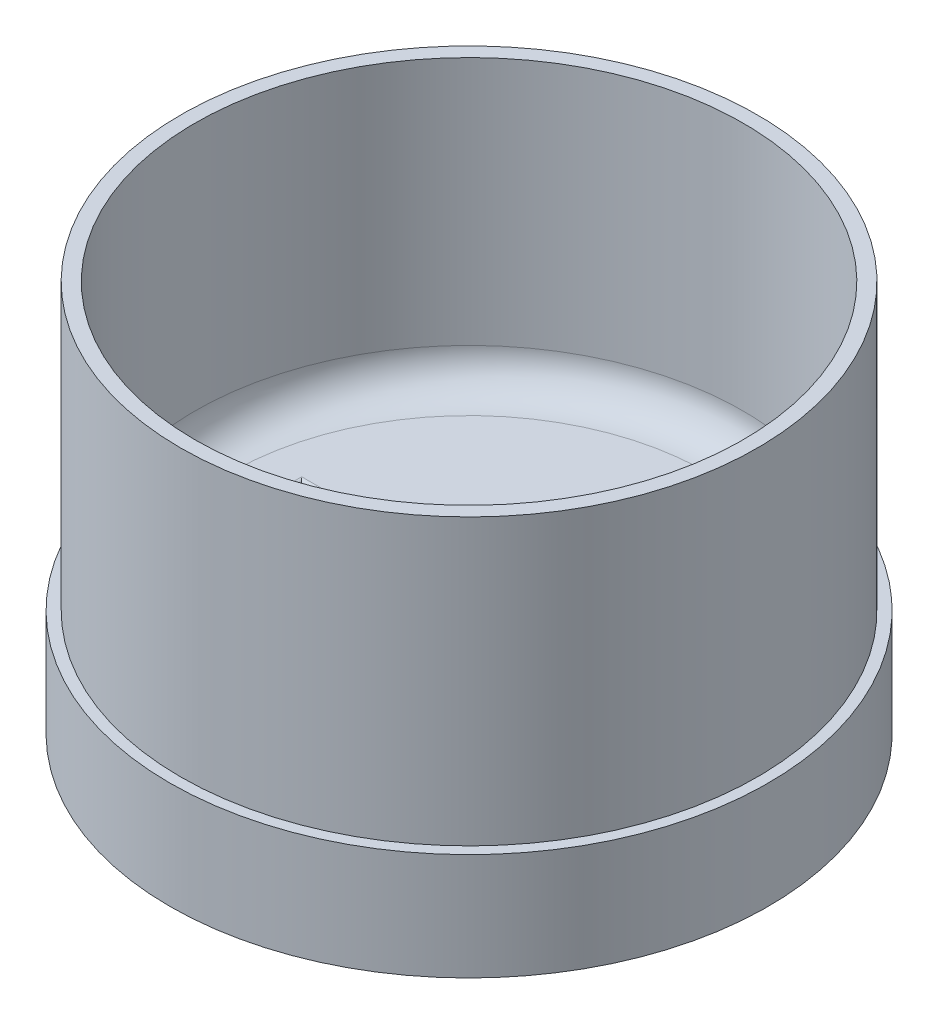
SolidWorks part; units mm, degrees
ref_plane "Front Plane" through (0, 0, 0) normal (0, 0, 1) x (1, 0, 0)
ref_plane "Top Plane" through (0, 0, 0) normal (0, 1, 0) x (1, 0, 0)
ref_plane "Right Plane" through (0, 0, 0) normal (1, 0, 0) x (0, 0, -1)
sketch "Sketch1" plane through (0, 0, 0) normal (0, 1, 0) x (1, 0, 0)
  circle A0 centre (0, 0) radius 84
  circle A1 centre (0, 0) radius 79
extrude "Boss-Extrude1" add sketch "Sketch1" along normal blind 25
sketch "Sketch2" plane through (0, 25, 0) normal (0, 1, 0) x (1, 0, 0)
  circle A0 centre (0, 0) radius 84
extrude "Boss-Extrude2" add sketch "Sketch2" along normal blind 5
sketch "Sketch3" plane through (0, 30, 0) normal (0, 1, 0) x (1, 0, 0)
  circle A0 centre (0, 0) radius 81
  circle A1 centre (0, 0) radius 77
extrude "Boss-Extrude3" add sketch "Sketch3" along normal blind 80
fillet "Fillet1" radius 10 2 edges at (0, 25, 79) (0, 30, 77)
sketch "Sketch4" plane through (0, 25, 0) normal (0, -1, 0) x (1, 0, 0)
  line L1 (7, -3.5) -> (7, 3.5)
  line L2 (7, 3.5) -> (-7, 3.5)
  line L3 (-7, 3.5) -> (-7, -3.5)
  line L4 (-7, -3.5) -> (7, -3.5)
  point P4 (0, 0)
  point P8 (7, 0)
extrude "Cut-Extrude1" cut sketch "Sketch4" against normal up to next
sketch "Sketch5" plane through (0, 30, 0) normal (0, 1, 0) x (1, 0, 0)
  line L0 (0, 0) -> (-45, 0) construction
  line L1 (-45, -8) -> (-45, 8)
  line L2 (-45, 8) -> (-55, 8)
  line L3 (-55, 8) -> (-55, -8)
  line L4 (-55, -8) -> (-45, -8)
  point P7 (-45, 0)
extrude "Cut-Extrude2" cut sketch "Sketch5" against normal up to next
fillet "Fillet2" radius 1 16 edges at (-7, 25, 0) (0, 25, 3.5) (7, 25, 0) (0, 25, -3.5) (-7, 30, 0) (0, 30, 3.5) (7, 30, 0) (0, 30, -3.5) (-50, 30, -8) (-55, 30, 0) (-45, 30, 0) (-50, 30, 8) (-50, 25, -8) (-55, 25, 0) (-50, 25, 8) (-45, 25, 0)
